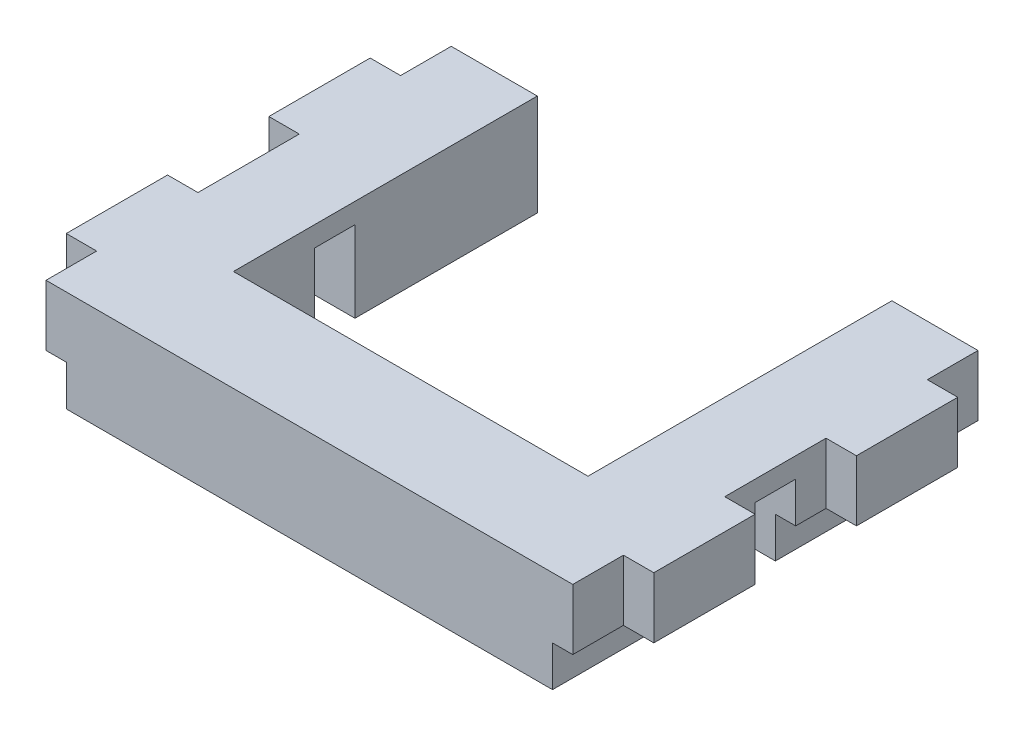
SolidWorks part; units mm, degrees
ref_plane "Front Plane" through (0, 0, 0) normal (0, 0, 1) x (1, 0, 0)
ref_plane "Top Plane" through (0, 0, 0) normal (0, 1, 0) x (1, 0, 0)
ref_plane "Right Plane" through (0, 0, 0) normal (1, 0, 0) x (0, 0, -1)
sketch "Sketch1" plane through (0, 0, 0) normal (0, 0, 1) x (1, 0, 0)
  line L0 (24, -3) -> (29, -3)
  line L1 (-24, -7) -> (24, -7)
  line L2 (-24, -7) -> (-24, -3)
  line L4 (24, -7) -> (24, -3)
  line L5 (-29, -3) -> (-24, -3)
  line L6 (-29, -3) -> (-29, 3)
  line L7 (-29, 3) -> (29, 3)
  line L8 (29, -3) -> (29, 3)
  line L9 (-29, 3) -> (29, -3) construction
  line L10 (0, -7) -> (0, 0) construction
  dimension "D1" = 10
  dimension "D2" = 48
  dimension "D3" = 5
  dimension "D4" = 4
extrude "Boss-Extrude1" add sketch "Sketch1" along normal blind 40
sketch "Sketch2" plane through (0, 3, 0) normal (0, 1, 0) x (1, 0, 0)
  line L0 (0, 0) -> (0, -15) construction
  line L1 (-17.5, 0) -> (17.5, 0)
  line L2 (-17.5, 0) -> (-17.5, -30)
  line L3 (-17.5, -30) -> (17.5, -30)
  line L4 (17.5, 0) -> (17.5, -30)
  line L5 (-17.5, 0) -> (17.5, -30) construction
  line L6 (-17.5, -30) -> (17.5, 0) construction
  line L7 (29, 0) -> (-29, 0) construction
  line L8 (29, -40) -> (29, 0) construction
  line L9 (26, -25) -> (29, -25)
  line L10 (26, -25) -> (26, -15)
  line L11 (26, -15) -> (29, -15)
  line L12 (29, -25) -> (29, -15)
  line L13 (-29, -25) -> (-26, -25)
  line L17 (29, -5) -> (26, -5) construction
  line L18 (26, -15) -> (29, -15) construction
  line L19 (26, -35) -> (29, -35) construction
  line L20 (29, -40) -> (26, -40)
  line L21 (29, -40) -> (29, -35)
  line L22 (29, -35) -> (26, -35)
  line L23 (26, -40) -> (26, -35)
  line L24 (-29, -40) -> (-26, -40)
  line L25 (-29, -40) -> (-29, -35)
  line L26 (-29, -25) -> (-29, -15)
  line L27 (-29, -15) -> (-26, -15)
  line L28 (-26, -25) -> (-26, -15)
  line L29 (-84, -25) -> (-81, -25)
  line L30 (-84, -25) -> (-84, -15)
  line L31 (-84, -15) -> (-81, -15)
  line L32 (-81, -25) -> (-81, -15)
  line L33 (26, -5) -> (29, -5)
  line L34 (26, -5) -> (26, 5)
  line L35 (26, 5) -> (29, 5)
  line L36 (29, -5) -> (29, 5)
  line L37 (-29, -5) -> (-26, -5)
  line L38 (-29, -5) -> (-29, 5)
  line L39 (-29, 5) -> (-26, 5)
  line L40 (-26, -5) -> (-26, 5)
  line L41 (-84, -5) -> (-81, -5)
  line L42 (-84, -5) -> (-84, 5)
  line L43 (-84, 5) -> (-81, 5)
  line L44 (-81, -5) -> (-81, 5)
  line L45 (-29, -35) -> (-26, -35)
  line L46 (-26, -40) -> (-26, -35)
  point P0 (0, -15)
  dimension "D1" = 30
  dimension "D2" = 35
  dimension "D4" = 3
  dimension "D5" = 10
  dimension "D6" = 3
  dimension "D7" = 2
extrude "Cut-Extrude1" cut sketch "Sketch2" against normal through all
sketch "Sketch3" plane through (0, -7, 0) normal (0, -1, 0) x (1, 0, 0)
  line L0 (29, 15) -> (29, 5) construction
  line L1 (29, 18) -> (-29, 18)
  line L2 (29, 18) -> (29, 22)
  line L3 (29, 22) -> (-29, 22)
  line L4 (-29, 18) -> (-29, 22)
  line L5 (29, 18) -> (-29, 22) construction
  line L6 (29, 22) -> (-29, 18) construction
  line L7 (17.5, 0) -> (24, 0) construction
  point P0 (0, 20)
  dimension "D1" = 4
  dimension "D2" = 20
extrude "Cut-Extrude2" cut sketch "Sketch3" against normal blind 8
